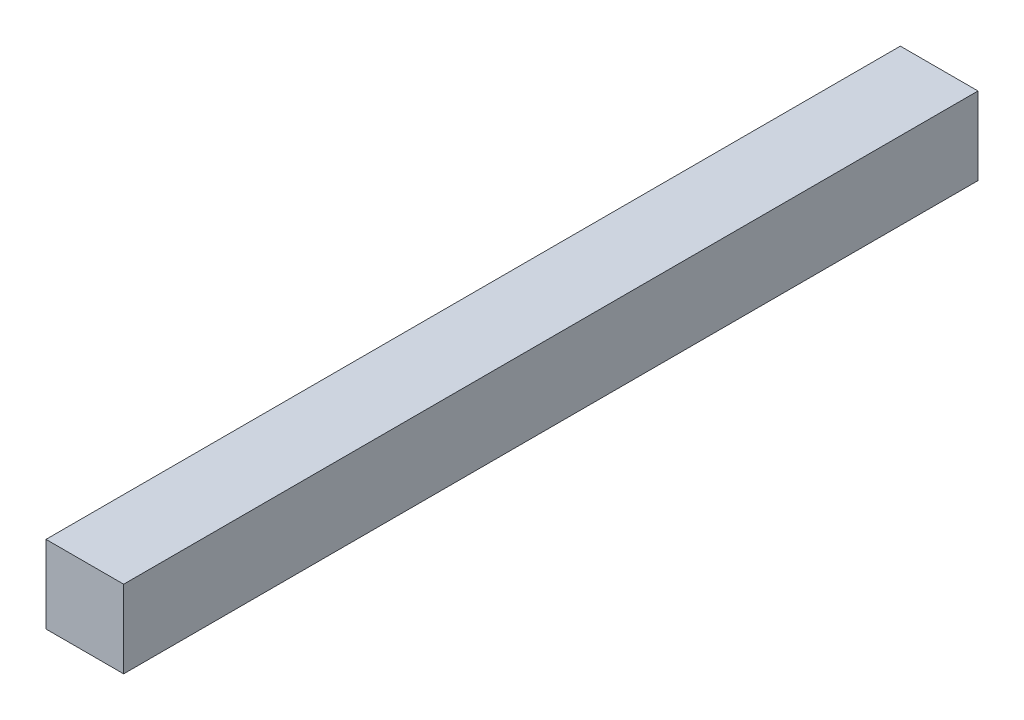
SolidWorks part; units mm, degrees
ref_plane "Front Plane" through (0, 0, 0) normal (0, 0, 1) x (1, 0, 0)
ref_plane "Top Plane" through (0, 0, 0) normal (0, 1, 0) x (1, 0, 0)
ref_plane "Right Plane" through (0, 0, 0) normal (1, 0, 0) x (0, 0, -1)
sketch "Sketch1" plane through (0, 0, 0) normal (0, 0, 1) x (1, 0, 0)
  line L1 (-15, -15) -> (15, -15)
  line L2 (-15, -15) -> (-15, 15)
  line L3 (-15, 15) -> (15, 15)
  line L4 (15, -15) -> (15, 15)
  line L5 (-15, -15) -> (15, 15) construction
  line L6 (-15, 15) -> (15, -15) construction
  point P0 (0, 0)
  dimension "D1" = 30
  dimension "D2" = 30
extrude "Boss-Extrude1" add sketch "Sketch1" along normal mid plane 330
